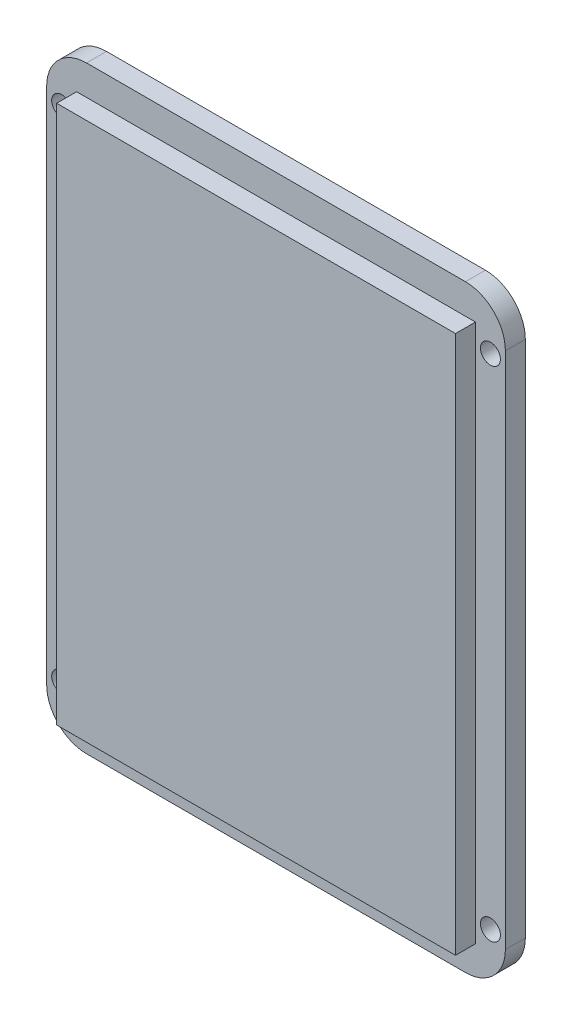
SolidWorks part; units mm, degrees
ref_plane "Plan de face" through (0, 0, 0) normal (0, 0, 1) x (1, 0, 0)
ref_plane "Plan de dessus" through (0, 0, 0) normal (0, 1, 0) x (1, 0, 0)
ref_plane "Plan de droite" through (0, 0, 0) normal (1, 0, 0) x (0, 0, -1)
sketch "Esquisse1" plane through (0, 0, 0) normal (0, 0, 1) x (1, 0, 0)
  line L1 (0, 0) -> (46, 0)
  line L2 (0, 0) -> (0, 60)
  line L3 (0, 60) -> (46, 60)
  line L4 (46, 0) -> (46, 60)
  line L5 (3, 57) -> (43, 57)
  line L6 (3, 57) -> (3, 3)
  line L7 (3, 3) -> (43, 3)
  line L8 (43, 57) -> (43, 3)
  dimension "D1" = 54
  dimension "D2" = 3
  dimension "D3" = 40
  dimension "D4" = 3
  dimension "D5" = 3
  dimension "D6" = 3
extrude "Boss.-Extru.1" add sketch "Esquisse1" along normal blind 4 contours L8 L5 L6 L7
sketch "Esquisse2" plane through (0, 0, 0) normal (0, 0, 1) x (1, 0, 0)
  line L0 (3, 57) -> (43, 57) construction
  line L1 (0, 60) -> (46, 60)
  line L2 (0, 60) -> (0, 0)
  line L3 (0, 0) -> (46, 0)
  line L4 (46, 60) -> (46, 0)
  line L5 (43, 57) -> (43, 3) construction
  line L6 (3, 3) -> (43, 3) construction
  line L7 (3, 57) -> (3, 3) construction
  dimension "D1" = 3
  dimension "D2" = 3
  dimension "D3" = 3
  dimension "D4" = 3
extrude "Boss.-Extru.2" add sketch "Esquisse2" along normal blind 2
fillet "Congé1" radius 4 4 edges at (0, 0, 1) (46, 0, 1) (46, 60, 1) (0, 60, 1)
sketch "Esquisse3" plane through (0, 0, 0) normal (0, 0, 1) x (1, 0, 0)
  line L0 (46, 4) -> (46, 56) construction
  line L1 (0, 56) -> (0, 4) construction
  line L2 (42, 60) -> (4, 60) construction
  line L3 (4, 0) -> (42, 0) construction
  circle A0 centre (44.5, 5) radius 1
  circle A1 centre (1.5, 5) radius 1
  circle A2 centre (1.5, 55) radius 1
  circle A3 centre (44.5, 55) radius 1
  dimension "D1" = 2
  dimension "D2" = 2
  dimension "D3" = 2
  dimension "D4" = 2
  dimension "D6" = 1.5
  dimension "D7" = 1.5
  dimension "D9" = 5
  dimension "D10" = 5
  dimension "D5" = 1.5
  dimension "D8" = 1.5
  dimension "D11" = 5
  dimension "D12" = 5
extrude "Enlèv. mat.-Extru.1" cut sketch "Esquisse3" along normal through all
